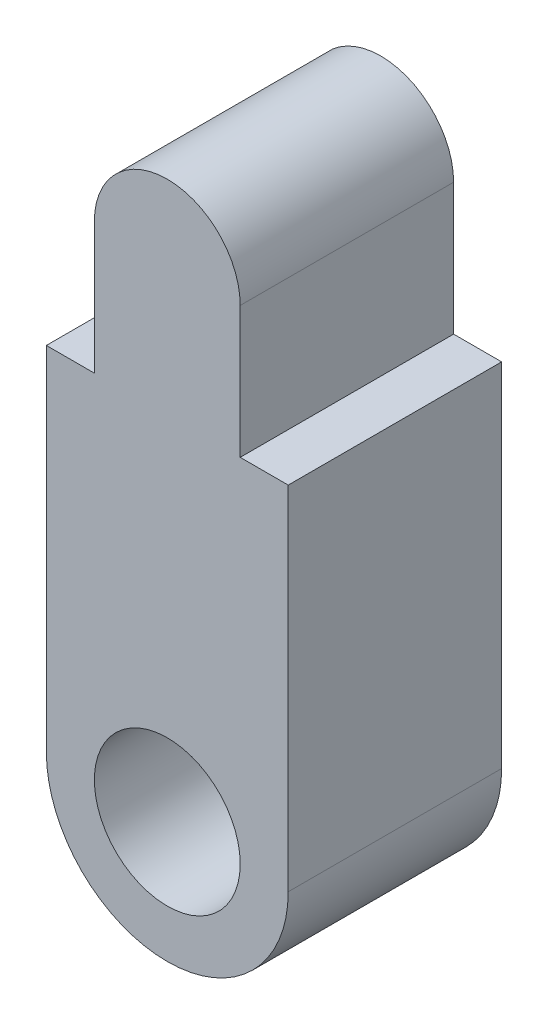
SolidWorks part; units mm, degrees
ref_plane "Front Plane" through (0, 0, 0) normal (0, 0, 1) x (1, 0, 0)
ref_plane "Top Plane" through (0, 0, 0) normal (0, 1, 0) x (1, 0, 0)
ref_plane "Right Plane" through (0, 0, 0) normal (1, 0, 0) x (0, 0, -1)
sketch "Sketch1" plane through (0, 0, 0) normal (0, 0, 1) x (1, 0, 0)
  line L0 (0, 0) -> (0, -68) construction
  line L1 (10.25, 0) -> (10.25, -68)
  line L2 (-10.25, 0) -> (-10.25, -68)
  line L3 (0, 0) -> (0, -68) construction
  line L4 (17, 0) -> (17, -68)
  line L5 (-17, 0) -> (-17, -68)
  line L7 (-17, 0) -> (17, 0)
  line L8 (-17, 0) -> (-17, -13.4932)
  line L9 (-17, -13.4932) -> (17, -13.4932)
  line L10 (17, 0) -> (17, -13.4932)
  line L11 (-17, -13.4932) -> (17, -13.4932)
  line L12 (-17, -13.4932) -> (-17, -18.4932)
  line L13 (-17, -18.4932) -> (17, -18.4932)
  line L14 (17, -13.4932) -> (17, -18.4932)
  arc A0 (10.25, 0) -> (-10.25, 0) centre (0, 0) ccw
  arc A1 (-10.25, -68) -> (10.25, -68) centre (0, -68) ccw
  arc A2 (17, 0) -> (-17, 0) centre (0, 0) ccw
  arc A3 (-17, -68) -> (17, -68) centre (0, -68) ccw
  circle A4 centre (0, -68) radius 10.25
  circle A5 centre (0, 0) radius 10.25
  point P3 (0, -34)
  point P10 (0, -34)
  dimension "D2" = 10.25
  dimension "D3" = 17
  dimension "D1" = 68
  dimension "D4" = 5
extrude "Boss-Extrude1" add sketch "Sketch1" along normal blind 30 contours L5 A3 L4 L13 L1 A1 L2 | A4 L1 L13 L2 | L2 L13 L1 L9 | A5 L2 L9 L1 | L7 A5 | L7 A0
